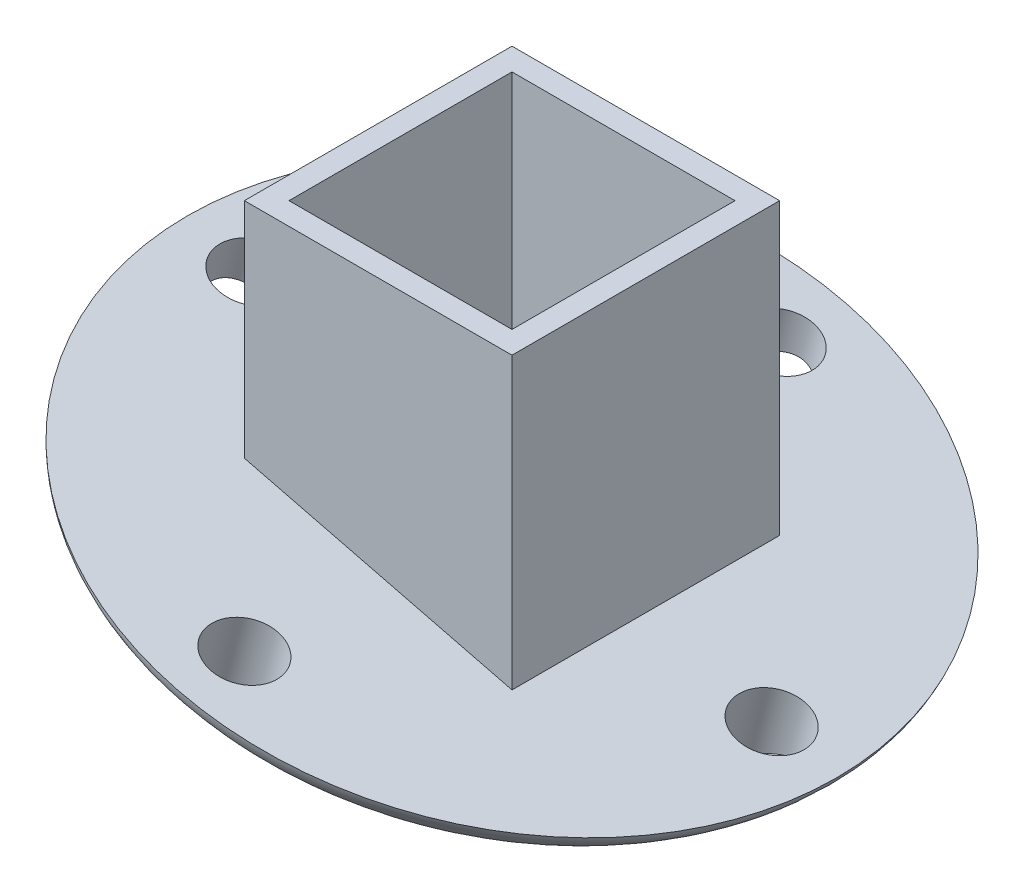
SolidWorks part; units mm, degrees
material "陶瓷"
ref_plane "前视基准面" through (0, 0, 0) normal (0, 0, 1) x (1, 0, 0)
ref_plane "上视基准面" through (0, 0, 0) normal (0, 1, 0) x (1, 0, 0)
ref_plane "右视基准面" through (0, 0, 0) normal (1, 0, 0) x (0, 0, -1)
other "Configuration Table"
sketch "草图1" plane through (0, 0, 0) normal (0, 1, 0) x (1, 0, 0)
  line L1 (-5, -5) -> (5, -5)
  line L2 (-5, -5) -> (-5, 5)
  line L3 (-5, 5) -> (5, 5)
  line L4 (5, -5) -> (5, 5)
  line L5 (-5, -5) -> (5, 5) construction
  line L6 (-5, 5) -> (5, -5) construction
  line L7 (-6, 6) -> (6, 6)
  line L8 (-6, 6) -> (-6, -6)
  line L9 (-6, -6) -> (6, -6)
  line L10 (6, 6) -> (6, -6)
  line L11 (-6, 6) -> (6, -6) construction
  line L12 (-6, -6) -> (6, 6) construction
  point P0 (0, 0)
  point P6 (0, 0)
extrude "凸台-拉伸1" add sketch "草图1" along normal blind 10
sketch "草图2" plane through (6, 0, 0) normal (1, 0, 0) x (0, 0, -1)
  line L0 (-6, 0) -> (6, 0)
  line L1 (6, 0) -> (6, -3)
  line L2 (6, -3) -> (-6, -3)
  line L3 (-6, -3) -> (-6, 0)
extrude "凸台-拉伸2" add sketch "草图2" against normal blind 12
sketch "草图3" plane through (0, 0, 6) normal (0, 0, 1) x (1, 0, 0)
  line L0 (6, -3) -> (6, 0)
  line L1 (6, 10) -> (6, -3) construction
  line L2 (6, 0) -> (-6, 0)
  line L3 (-6, 10) -> (-6, -3) construction
  line L4 (-6, 0) -> (6, -3)
  line L5 (-6, 0) -> (-6, -3)
  line L6 (-6, -3) -> (6, -3)
  line M4 (-6, 10) -> (-6, -3)
  line M5 (-6, -3) -> (6, -3)
extrude "切除-拉伸1" cut sketch "草图3" against normal blind 12 contours L4 M4 M5
ref_plane "基准面1" through (0, 0, 0) normal (0, 0, 1) x (1, 0, 0)
sketch "草图12" plane through (0, 0, 0) normal (0, 0, 1) x (1, 0, 0)
  line L0 (-6, 0) -> (6, -3)
  line L1 (6, -3) -> (0, -1.5)
  line L2 (0, -1.5) -> (14.5521, -5.138)
  line L3 (0, -1.5) -> (-1.2127, -6.3507)
  spline S0 degree 3 poles (-1.2127, -6.3507) (4.8759, -8.1818) (13.5705, -7.2899) (14.5521, -5.138) knots 0 0 0 0 1 1 1 1
revolve "旋转2" add sketch "草图12" angle 360 about L3
sketch "草图13" plane through (-0.3529, -1.4118, 0) normal (0.2425, 0.9701, 0) x (0.9701, -0.2425, 0)
  circle A3 centre (0.364, 12.0002) radius 1.5
  circle A4 centre (12.364, 0.0002) radius 1.5
  circle A5 centre (0.364, -11.9998) radius 1.5
  circle A6 centre (-11.636, 0.0002) radius 1.5
extrude "切除-拉伸3" cut sketch "草图13" against normal blind 5
